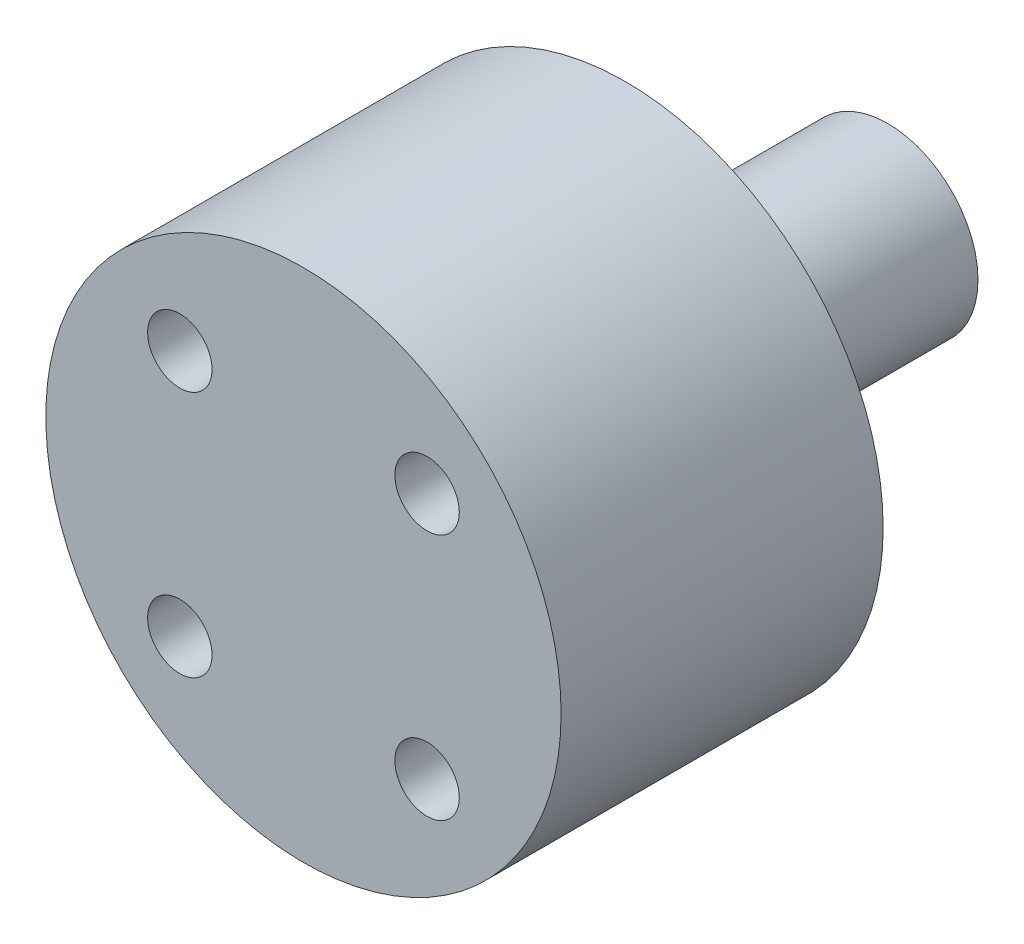
SolidWorks part; units mm, degrees
ref_plane "Plan de face" through (0, 0, 0) normal (0, 0, 1) x (1, 0, 0)
ref_plane "Plan de dessus" through (0, 0, 0) normal (0, 1, 0) x (1, 0, 0)
ref_plane "Plan de droite" through (0, 0, 0) normal (1, 0, 0) x (0, 0, -1)
sketch "Esquisse1" plane through (0, 0, 0) normal (0, 0, 1) x (1, 0, 0)
  circle A0 centre (0, 0) radius 14
  circle A1 centre (-6.7175, 6.7175) radius 1.75
  circle A2 centre (6.7175, 6.7175) radius 1.75
  circle A3 centre (6.7175, -6.7175) radius 1.75
  circle A4 centre (-6.7175, -6.7175) radius 1.75
  point P5 (0, 0)
  point P14 (0, 0)
  dimension "D1" = 28
  dimension "D2" = 3.5
  dimension "D4" = 19
  dimension "D3" = 4
extrude "Boss.-Extru.1" add sketch "Esquisse1" along normal blind 17.5 contours A0 | A4 | A1 | A3 | A2
sketch "Esquisse2" plane through (0, 0, 0) normal (0, 0, -1) x (-1, 0, 0)
  circle A0 centre (0, 0) radius 4.9041
extrude "Boss.-Extru.2" add sketch "Esquisse2" along normal blind 14.25
